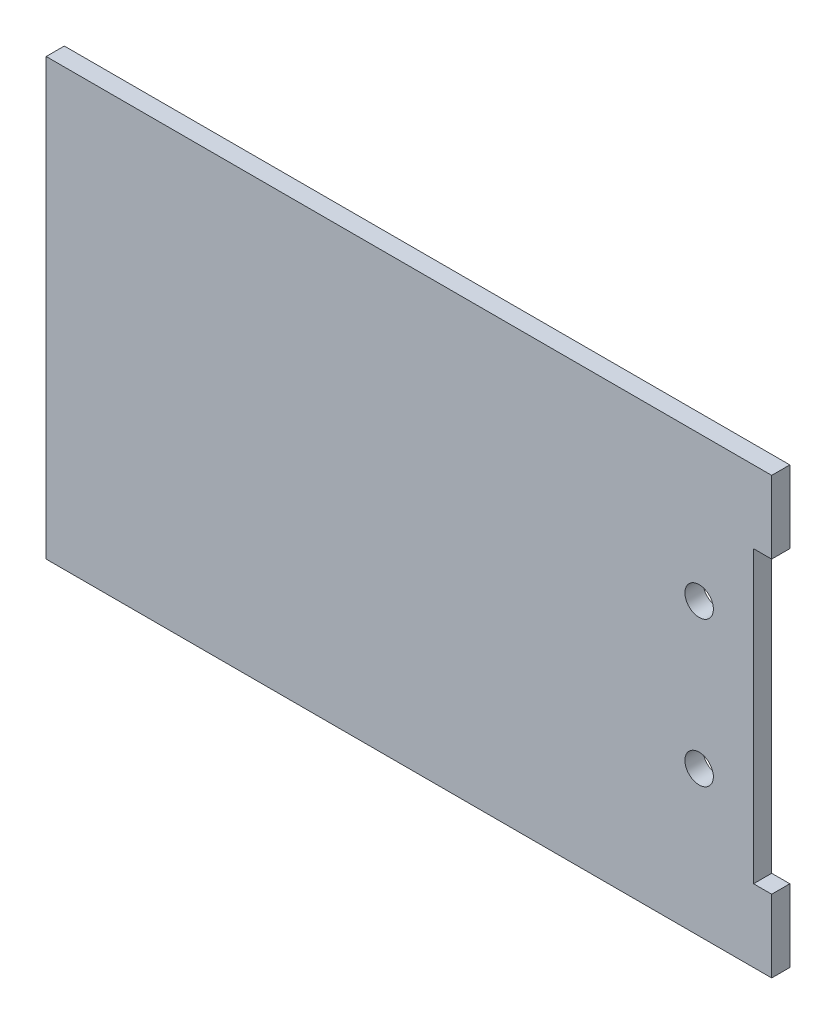
SolidWorks part; units mm, degrees
ref_plane "Front Plane" through (0, 0, 0) normal (1, 0, 0) x (0, 1, 0)
ref_plane "Top Plane" through (0, 0, 0) normal (0, 0, 1) x (0, 1, 0)
ref_plane "Right Plane" through (0, 0, 0) normal (0, 1, 0) x (-1, 0, 0)
sketch "Sketch1" plane through (0, 0, 0) normal (0, 0, 1) x (0, 1, 0)
  line L1 (-38.1, -63.5) -> (38.1, -63.5)
  line L2 (-38.1, -63.5) -> (-38.1, 63.5)
  line L3 (-38.1, 63.5) -> (38.1, 63.5)
  line L4 (38.1, -63.5) -> (38.1, 63.5)
  line L5 (-38.1, -63.5) -> (38.1, 63.5) construction
  line L6 (-38.1, 63.5) -> (38.1, -63.5) construction
  point P1 (0, 0)
  dimension "D1" = 76.2
  dimension "D2" = 127
extrude "Boss-Extrude1" add sketch "Sketch1" along normal blind 3.175
sketch "Sketch2" plane through (0, 0, 3.175) normal (0, 0, 1) x (1, 0, 0)
  line L11 (-63.5, -38.1) -> (63.5, -38.1) construction
  line L12 (63.5, -38.1) -> (63.5, 38.1) construction
  point P8 (50.8, -12.7)
  point P9 (50.8, 12.7)
  dimension "D1" = 25.4
  dimension "D2" = 12.7
  dimension "D3" = 25.4
hole_wizard "#9 (0.196) Diameter Hole1" positions "Sketch2" profile "Sketch3" hole size "#9" standard "ANSI Inch" end condition through all
sketch "Sketch3" plane through (50.8, -12.7, 3.175) normal (1, 0, 0) x (0, -1, 0)
  line L0 (0, 0) -> (0, 3.175)
  line L1 (0, 3.175) -> (2.4892, 3.175)
  line L2 (2.4892, 3.175) -> (2.4892, 0)
  line L5 (2.4892, 0) -> (0, 0)
  line L11 (0, -6.35) -> (0, 107.95) construction
  dimension "Thru Hole Dia." = 4.9784
  dimension "Thru Hole Depth" = 3.175
sketch "Sketch4" plane through (0, 0, 3.175) normal (0, 0, 1) x (1, 0, 0)
  line L0 (63.5, 25.4) -> (60.325, 25.4)
  line L1 (63.5, -38.1) -> (63.5, 38.1) construction
  line L2 (60.325, 25.4) -> (60.325, -25.4)
  line L3 (60.325, -25.4) -> (63.5, -25.4)
  line L4 (-63.5, -38.1) -> (63.5, -38.1) construction
  dimension "D1" = 3.175
  dimension "D2" = 50.8
  dimension "D3" = 12.7
extrude "Cut-Extrude1" cut sketch "Sketch4" against normal through all and the other way through all
